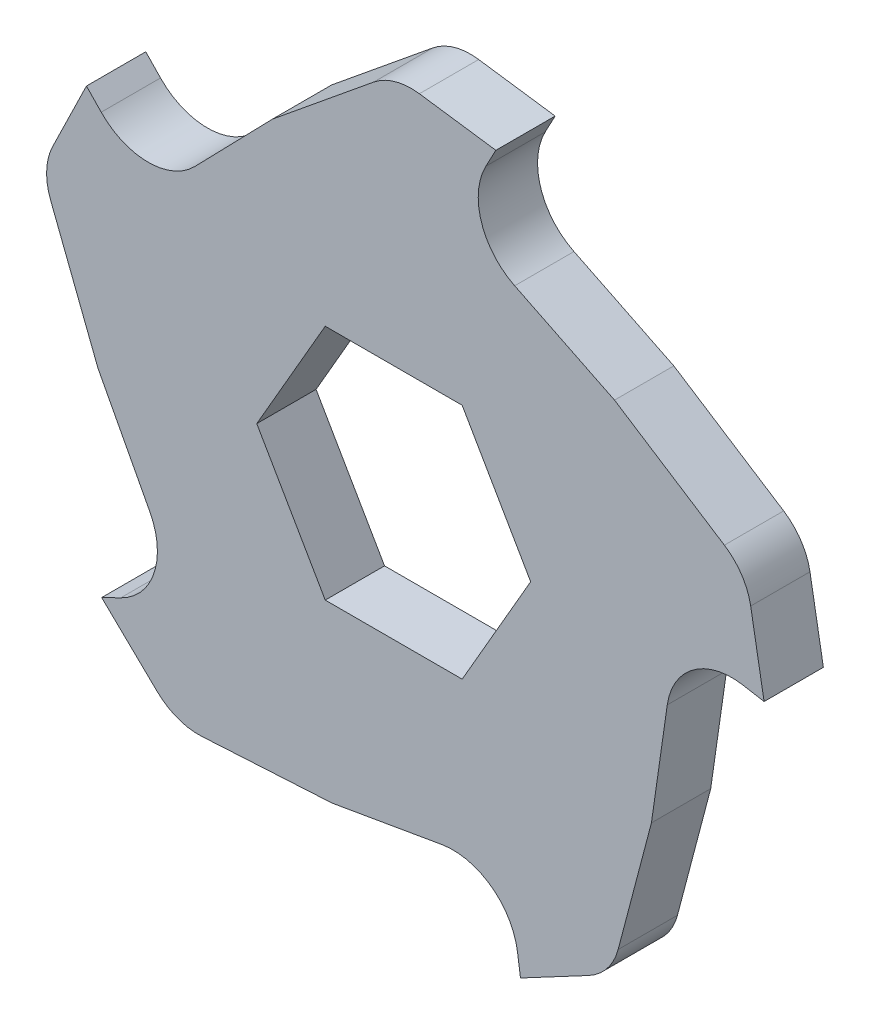
SolidWorks part; units mm, degrees
ref_plane "Front Plane" through (0, 0, 0) normal (0, 0, 1) x (1, 0, 0)
ref_plane "Top Plane" through (0, 0, 0) normal (0, 1, 0) x (1, 0, 0)
ref_plane "Right Plane" through (0, 0, 0) normal (1, 0, 0) x (0, 0, -1)
sketch "Sketch1" plane through (0, 0, 0) normal (0, 0, 1) x (1, 0, 0)
  line L0 (55, 0) -> (-55, 0) construction
  line L1 (23.094, -40) -> (46.188, 0)
  line L2 (46.188, 0) -> (23.094, 40)
  line L3 (23.094, 40) -> (-23.094, 40)
  line L4 (-23.094, 40) -> (-46.188, 0)
  line L5 (-46.188, 0) -> (-23.094, -40)
  line L6 (-23.094, -40) -> (23.094, -40)
  circle A0 centre (0, 0) radius 125
  circle A1 centre (0, 0) radius 40 construction
  point P3 (46.188, 0)
  dimension "D1" = 80
  dimension "D2" = 250
extrude "Boss-Extrude1" add sketch "Sketch1" along normal blind 20
sketch "Sketch3" plane through (0, 0, 20) normal (0, 0, 1) x (1, 0, 0)
  line L0 (8.6617, 123.7834) -> (34.45, 120.1591)
  line L1 (0, -11) -> (0, 11) construction
  line L2 (34.45, 120.1591) -> (31.0843, 113.8291)
  line L3 (40.8008, 83.7587) -> (74.4713, 67.2007)
  line L4 (-6.7741, 119.4673) -> (-40.8988, 91.5926)
  line L5 (111.5268, 43.36) -> (74.4713, 67.2007)
  line L6 (120.4016, 30.0134) -> (124.9237, 4.3673)
  line L7 (124.9237, 4.3673) -> (117.8634, 5.6122)
  line L8 (92.2673, -12.921) -> (86.9246, -50.0603)
  line L9 (75.7015, -92.6693) -> (86.9246, -50.0603)
  line L10 (65.7506, -105.2341) -> (42.7571, -117.4599)
  line L11 (42.7571, -117.4599) -> (41.7593, -110.3605)
  line L12 (16.2236, -91.7443) -> (-20.749, -98.1397)
  line L13 (-64.7407, -100.6328) -> (-20.749, -98.1397)
  line L14 (-79.7655, -95.0516) -> (-98.4984, -76.9615)
  line L15 (-98.4984, -76.9615) -> (-92.0547, -73.8188)
  line L16 (-82.2406, -43.7801) -> (-99.7482, -10.5934)
  line L17 (-115.7134, 30.4749) -> (-99.7482, -10.5934)
  line L18 (-115.0484, 46.4889) -> (-103.6324, 69.8951)
  line L19 (-103.6324, 69.8951) -> (-98.6523, 64.738)
  line L20 (-67.0511, 64.6867) -> (-40.8988, 91.5926)
  arc A0 (111.5268, 43.36) -> (120.4016, 30.0134) centre (100.7054, 26.5404) cw
  circle A1 centre (0, 0) radius 125 construction
  arc A2 (31.0843, 113.8291) -> (40.8008, 83.7587) centre (50.5091, 103.5007) ccw
  arc A3 (117.8634, 5.6122) -> (92.2673, -12.921) centre (114.0432, -16.0536) ccw
  arc A4 (41.7593, -110.3605) -> (16.2236, -91.7443) centre (19.9734, -113.4223) ccw
  arc A5 (-92.0547, -73.8188) -> (-82.2406, -43.7801) centre (-101.6989, -54.0453) ccw
  arc A6 (-98.6523, 64.738) -> (-67.0511, 64.6867) centre (-82.8268, 80.0205) ccw
  arc A7 (8.6617, 123.7834) -> (-6.7741, 119.4673) centre (5.8783, 103.978) ccw
  arc A8 (-115.7134, 30.4749) -> (-115.0484, 46.4889) centre (-97.0725, 37.7215) cw
  arc A9 (-64.7407, -100.6328) -> (-79.7655, -95.0516) centre (-65.8723, -80.6648) cw
  arc A10 (75.7015, -92.6693) -> (65.7506, -105.2341) centre (56.3611, -87.5751) cw
  point P7 (0, 0)
  point P10 (-40.8672, 91.5845)
  point P37 (0, 125.0007)
  point P41 (0, 0)
  point P42 (0, 0)
  point P43 (-40.8988, 91.5926)
  circle M26 centre (0, 0) radius 125
  dimension "D4" = 22
  dimension "D6" = 20
  dimension "D1" = 34.45
  dimension "D2" = 70
  dimension "D3" = 82
  dimension "D5" = 6.33
  dimension "D7" = 5
extrude "Cut-Extrude1" cut sketch "Sketch3" against normal blind 30 contours L19 A6 L20 L4 M26 | L2 A2 L3 L5 M26 | L7 A3 L8 L9 M26 | L11 A4 L12 L13 M26 | L15 A5 L16 L17 M26
